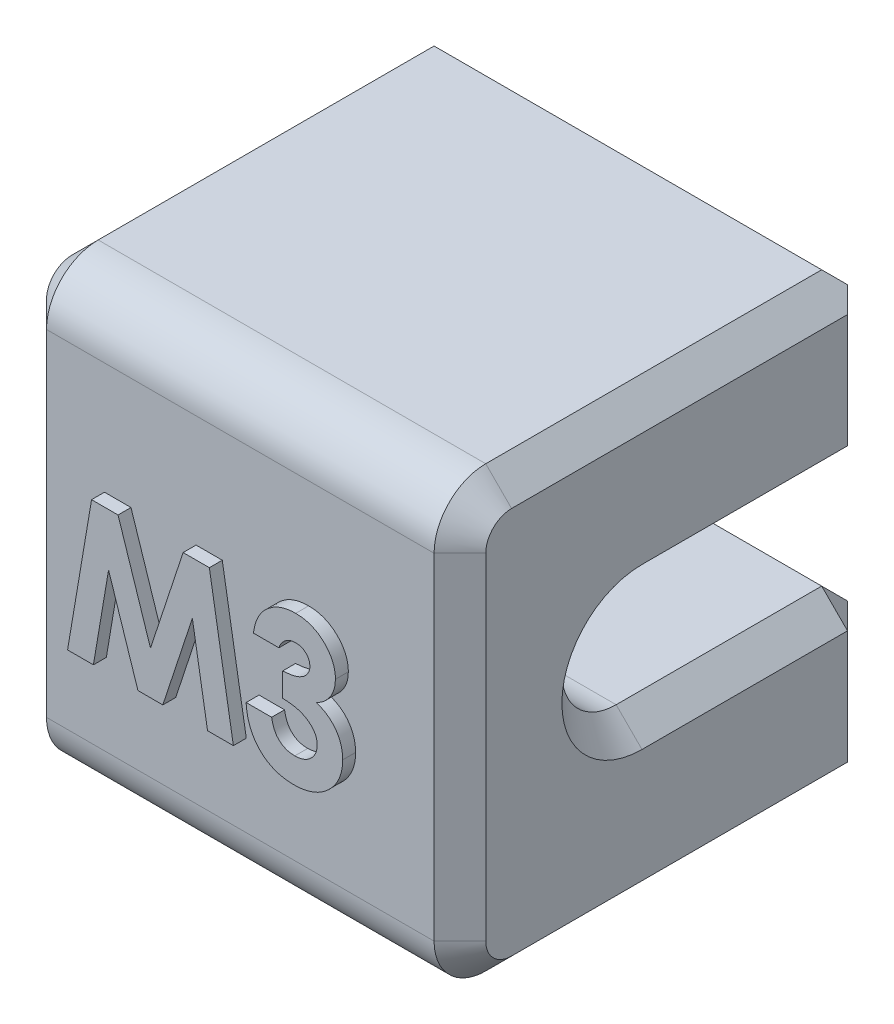
SolidWorks part; units mm, degrees
material "PETG"
ref_plane "Płaszczyzna przednia" through (0, 0, 0) normal (0, 0, 1) x (1, 0, 0)
ref_plane "Płaszczyzna górna" through (0, 0, 0) normal (0, 1, 0) x (1, 0, 0)
ref_plane "Płaszczyzna prawa" through (0, 0, 0) normal (1, 0, 0) x (0, 0, -1)
sketch "Sketch1" plane through (0, 0, 0) normal (0, 0, 1) x (1, 0, 0)
  line L1 (0, 0) -> (17, 0)
  line L2 (0, 0) -> (0, 17)
  line L3 (0, 17) -> (17, 17)
  line L4 (17, 0) -> (17, 17)
  dimension "D1" = 17
extrude "Boss-Extrude1" add sketch "Sketch1" along normal blind 16
sketch "Sketch2" plane through (0, 0, 0) normal (-1, 0, 0) x (0, 0, 1)
  line L0 (8.9538, 10.6) -> (0, 10.6)
  line L1 (0, 17) -> (0, 0) construction
  line L2 (0, 10.6) -> (0, 6.4)
  line L3 (0, 6.4) -> (8.9538, 6.4)
  line L4 (8.9538, 0) -> (8.9538, 8.5) construction
  line L5 (16, 0) -> (0, 0) construction
  line L6 (8.9538, 8.5) -> (8.9538, 17) construction
  line L7 (16, 17) -> (0, 17) construction
  arc A0 (8.9538, 6.4) -> (8.9538, 10.6) centre (8.9538, 8.5) ccw
  dimension "D1" = 4.2
extrude "Cut-Extrude1" cut sketch "Sketch2" against normal through all
chamfer "Chamfer1" distance 1 angle 45 14 edges at (8.5, 10.6, 0) (8.5, 6.4, 0) (8.5, 0, 0) (8.5, 17, 0) (17, 10.6, 4.4769) (0, 10.6, 4.4769) (17, 8.5, 11.0538) (0, 8.5, 11.0538) (17, 6.4, 4.4769) (0, 6.4, 4.4769) (0, 3.2, 0) (17, 3.2, 0) (0, 13.8, 0) (17, 13.8, 0)
fillet "Fillet1" radius 2 2 edges at (8.5, 0, 16) (8.5, 17, 16)
sketch "Sketch3" plane through (0, 0, 16) normal (0, 0, 1) x (1, 0, 0)
  text T0 "M3" font "Century Gothic" height 5.5
extrude "Boss-Extrude2" add sketch "Sketch3" along normal blind 0.5
chamfer "Chamfer3" distance 1 angle 45 10 edges at (17, 0, 7.5) (17, 0.5858, 15.4142) (17, 8.5, 16) (17, 16.4142, 15.4142) (17, 17, 7.5) (0, 0, 7.5) (0, 0.5858, 15.4142) (0, 8.5, 16) (0, 16.4142, 15.4142) (0, 17, 7.5)
